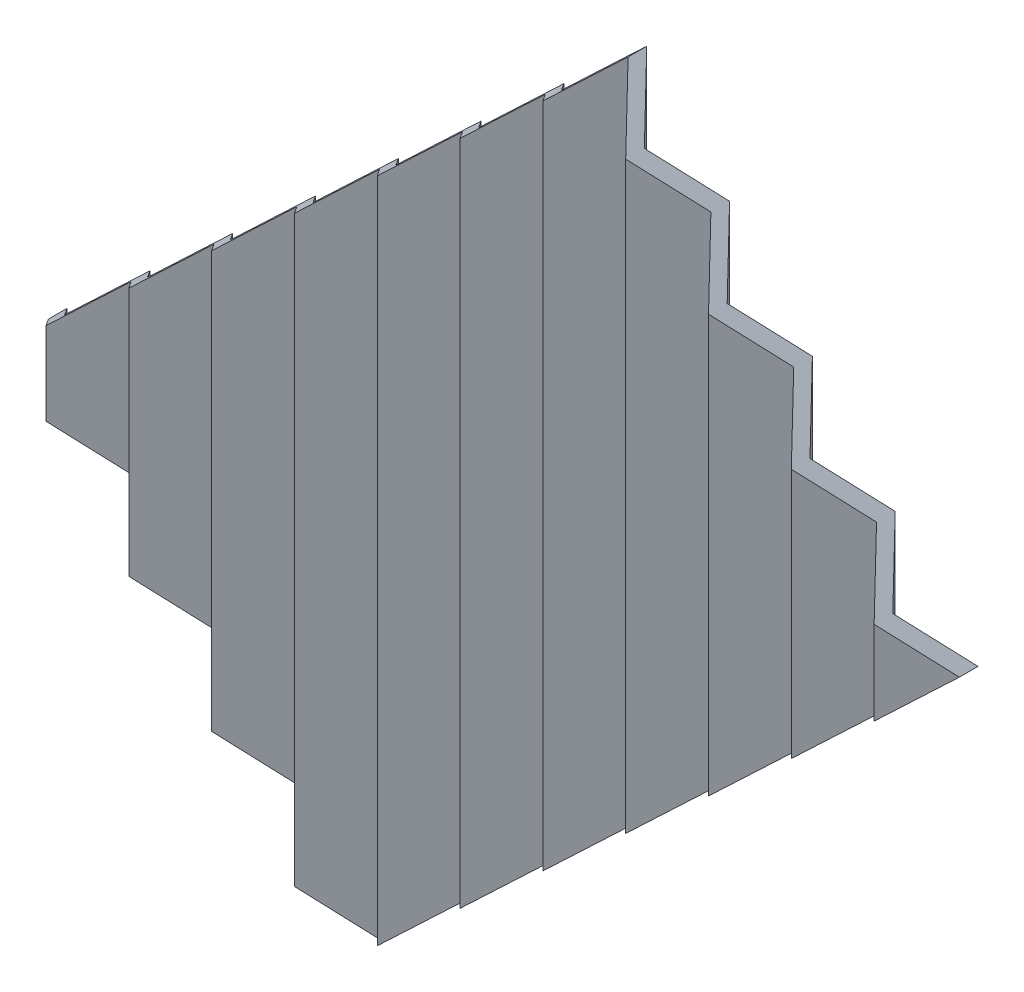
SolidWorks part; units mm, degrees
material "PET"
ref_plane "Plan de face" through (0, 0, 0) normal (0, 0, 1) x (1, 0, 0)
ref_plane "Plan de dessus" through (0, 0, 0) normal (0, 1, 0) x (1, 0, 0)
ref_plane "Plan de droite" through (0, 0, 0) normal (1, 0, 0) x (0, 0, -1)
sketch "Esquisse1" plane through (0, 0, 0) normal (0, 1, 0) x (1, 0, 0)
  line L1 (0, 0) -> (-6.6942, 0) construction
  line L2 (0, 0) -> (6.6158, 0) construction
  line L5 (0, 10) -> (6.6158, 3)
  line L6 (0, 10) -> (0, 7) construction
  line L7 (0, 7) -> (-6.6942, 0)
  line L8 (0, 7) -> (6.6158, 0)
  line L9 (-6.6942, 0) -> (-6.6942, 3)
  line L10 (0, 10) -> (-6.6942, 3)
  line L11 (6.6158, 3) -> (6.6158, 0)
  point P7 (0, 0)
  point P10 (0, 0)
  point P11 (0, 0)
  point P13 (0, 0)
  point P14 (0, 0)
  dimension "D1" = 13.31
  dimension "D2" = 3
  dimension "D3" = 10
extrude "Boss.-Extru.1" add sketch "Esquisse1" along normal blind 200 contours L10 L9 L7 L8 L11 L5
pattern_linear "Répétition linéaire1" count 15 spacing 13.31 along (1, 0, 0) of "Boss.-Extru.1"
surface "Surface-Plan2"
sketch "Esquisse4" plane through (0, 0, -10) normal (0, 0, 1) x (1, 0, 0)
  line L1 (66.55, 25.1471) -> (159.72, 108.219)
  line L2 (66.55, 25.1471) -> (13.31, 84.859)
  line L3 (13.31, 84.859) -> (106.48, 167.9308)
  line L4 (159.72, 108.219) -> (106.48, 167.9308)
  line L8 (159.72, 200) -> (159.72, 0) construction
  line L9 (106.48, 200) -> (106.48, 0) construction
  line L10 (13.31, 200) -> (13.31, 0) construction
  point P0 (93.17, 72.5235)
  point P1 (0, 0)
  point P2 (41.6961, 85.5452)
  point P3 (33.4107, 89.5216)
  point P4 (33.2358, 90.776)
  point P9 (0, 0)
  point P10 (19.0116, 86.3868)
  point P11 (0, 0)
  point P12 (0, 0)
  point P15 (13.31, 84.859)
  point P19 (0, 0)
  dimension "D1" = 80
  dimension "D2" = 124.8262
extrude "Enlèv. mat.-Extru.2" cut sketch "Esquisse4" along normal blind 150 flip side to cut
